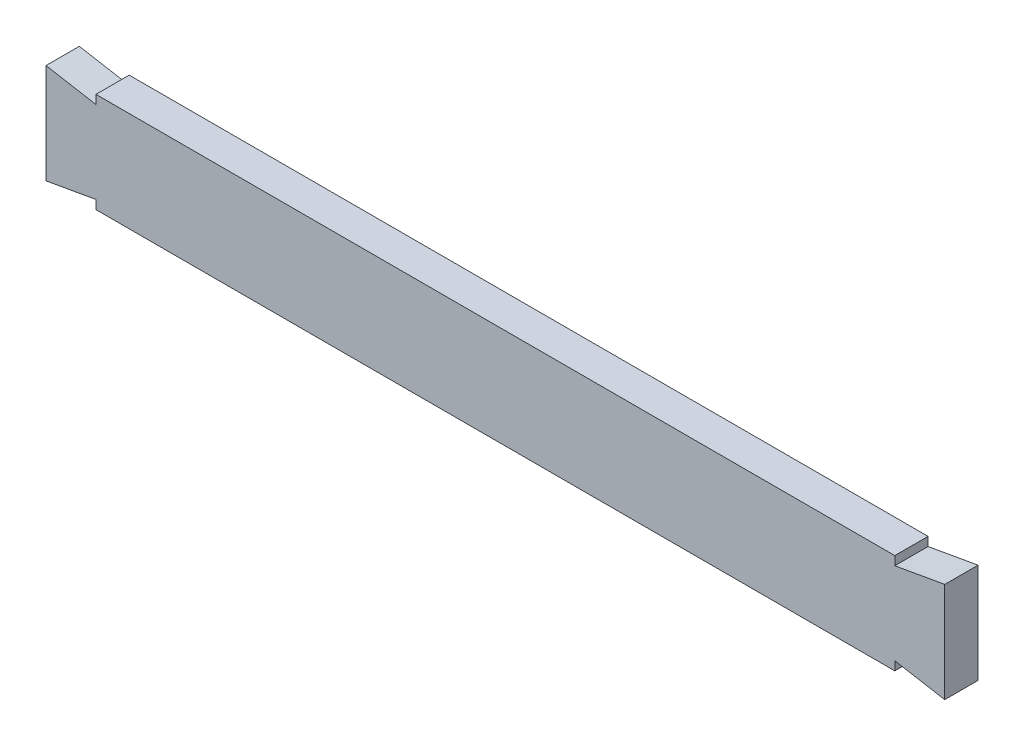
SolidWorks part; units mm, degrees
ref_plane "Plan de face" through (0, 0, 0) normal (0, 0, 1) x (1, 0, 0)
ref_plane "Plan de dessus" through (0, 0, 0) normal (0, 1, 0) x (1, 0, 0)
ref_plane "Plan de droite" through (0, 0, 0) normal (1, 0, 0) x (0, 0, -1)
sketch "Esquisse1" plane through (0, 0, 0) normal (0, 0, 1) x (1, 0, 0)
  line L1 (0, 0) -> (270, 0)
  line L2 (0, 0) -> (0, 30)
  line L3 (0, 30) -> (270, 30)
  line L4 (270, 0) -> (270, 30)
  dimension "D1" = 30
  dimension "D2" = 270
extrude "Boss.-Extru.1" add sketch "Esquisse1" along normal blind 10
sketch "Esquisse2" plane through (0, 0, 10) normal (0, 0, 1) x (1, 0, 0)
  line L0 (135, 0) -> (135, 30) construction
  line L1 (0, 0) -> (270, 0) construction
  line L2 (270, 30) -> (0, 30) construction
  line L3 (135, 15) -> (0, 15) construction
  line L4 (0, 30) -> (0, 0) construction
  line L5 (0, 30) -> (15, 27.3551)
  line L6 (15, 27.3551) -> (15, 30)
  line L7 (15, 30) -> (0, 30)
  line L8 (15, 2.6449) -> (15, 0)
  line L9 (0, 0) -> (15, 2.6449)
  line L10 (15, 0) -> (0, 0)
  line L11 (255, 0) -> (270, 0)
  line L12 (270, 0) -> (255, 2.6449)
  line L13 (255, 2.6449) -> (255, 0)
  line L14 (255, 30) -> (270, 30)
  line L15 (255, 27.3551) -> (255, 30)
  line L16 (270, 30) -> (255, 27.3551)
  dimension "D1" = 10
  dimension "D2" = 15
extrude "Enlèv. mat.-Extru.1" cut sketch "Esquisse2" against normal through all both and the other way through all
sketch "Esquisse3" plane through (270, 0, 0) normal (1, 0, 0) x (0, 0, -1)
  line L0 (-10, 15) -> (0, 15) construction
  line L1 (-10, 0) -> (-10, 30) construction
  line L2 (0, 0) -> (0, 30) construction
